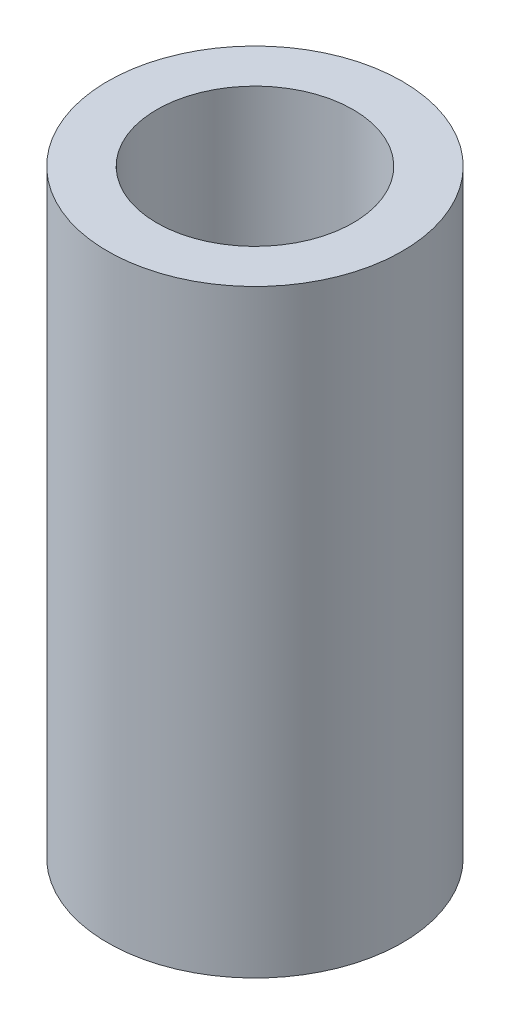
SolidWorks part; units mm, degrees
ref_plane "前视基准面" through (0, 0, 0) normal (0, 0, 1) x (1, 0, 0)
ref_plane "上视基准面" through (0, 0, 0) normal (0, 1, 0) x (1, 0, 0)
ref_plane "右视基准面" through (0, 0, 0) normal (1, 0, 0) x (0, 0, -1)
other "Configuration Table"
sketch "草图1" plane through (0, 0, 0) normal (0, 1, 0) x (1, 0, 0)
  circle A0 centre (0, 0) radius 5
  circle A1 centre (0, 0) radius 7.5
  dimension "D1" = 10
  dimension "D2" = 15
extrude "凸台-拉伸1" add sketch "草图1" along normal blind 30.5
